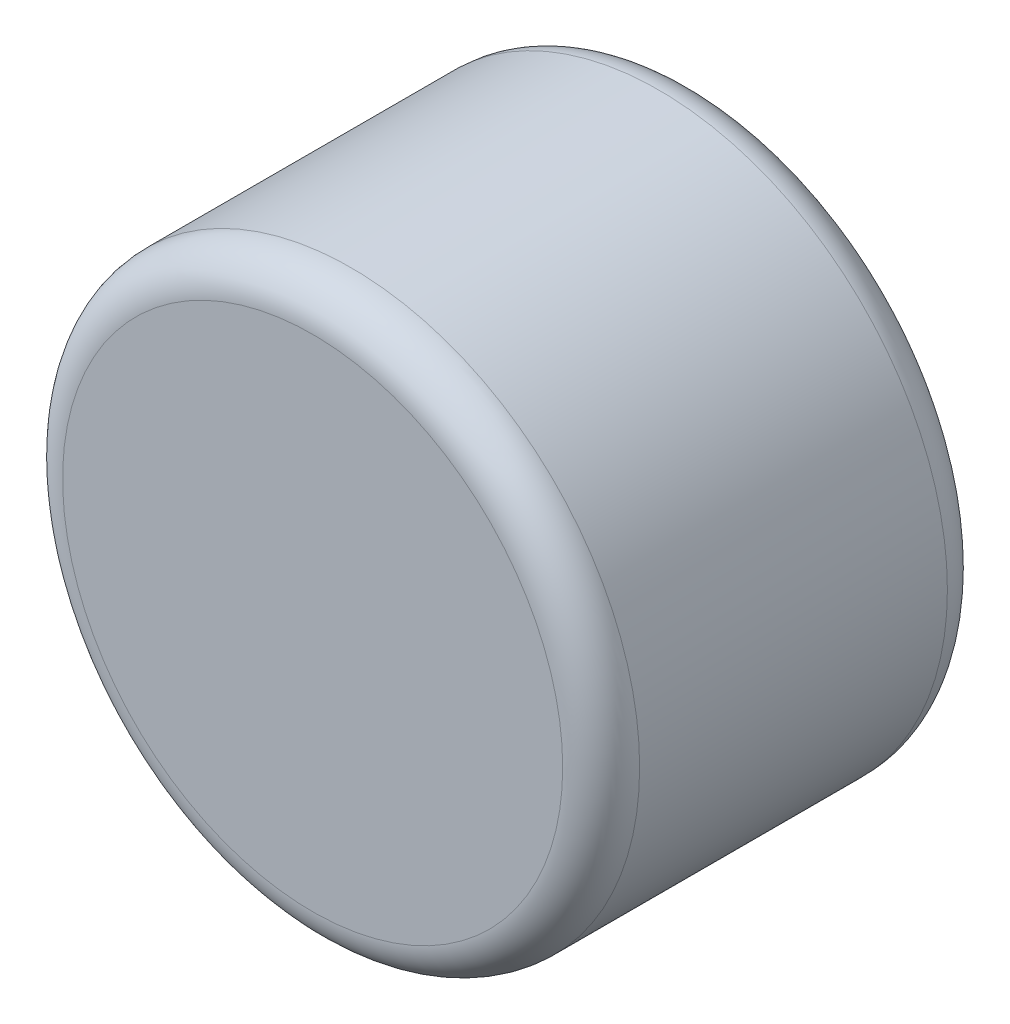
SolidWorks part; units mm, degrees
ref_plane "Front" through (0, 0, 0) normal (0, 0, 1) x (1, 0, 0)
ref_plane "Top" through (0, 0, 0) normal (0, 1, 0) x (1, 0, 0)
ref_plane "Right" through (0, 0, 0) normal (1, 0, 0) x (0, 0, -1)
sketch "Эскиз1" plane through (0, 0, 0) normal (0, 0, 1) x (1, 0, 0)
  circle A0 centre (0, 0) radius 1.5
  dimension "D1" = 3
extrude "Бобышка-Вытянуть1" add sketch "Эскиз1" along normal blind 2
fillet "Скругление1" radius 0.2 2 edges at (1.5, 0, 0) (1.5, 0, 2)
